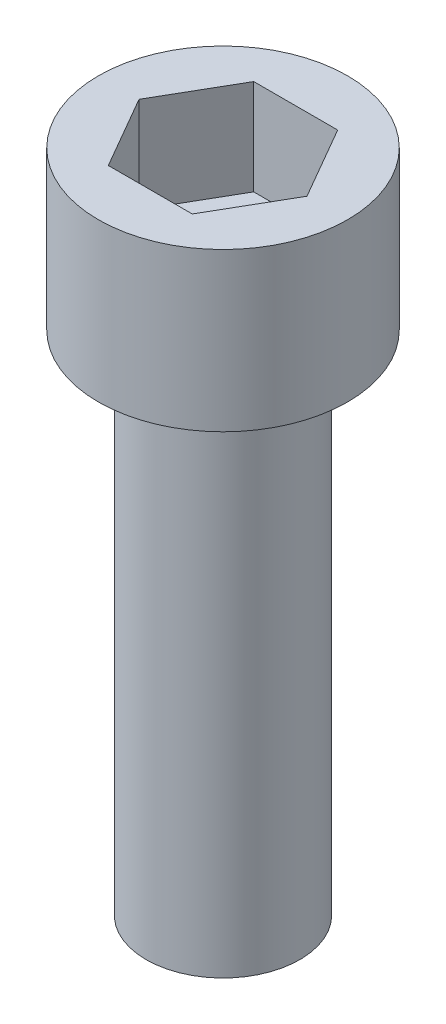
SolidWorks part; units mm, degrees
ref_plane "Front Plane" through (0, 0, 0) normal (0, 0, 1) x (1, 0, 0)
ref_plane "Top Plane" through (0, 0, 0) normal (0, 1, 0) x (1, 0, 0)
ref_plane "Right Plane" through (0, 0, 0) normal (1, 0, 0) x (0, 0, -1)
sketch "Sketch2" plane through (0, 0, 0) normal (1, 0, 0) x (0, 0, -1)
  line L0 (0, 0) -> (2.3495, 0)
  line L1 (2.3495, 0) -> (2.3495, 15.494)
  line L2 (2.3495, 15.494) -> (3.81, 15.494)
  line L3 (3.81, 15.494) -> (3.81, 20.32)
  line L4 (3.81, 20.32) -> (0, 20.32)
  line L5 (0, 20.32) -> (0, 0)
  dimension "D1" = 2.3495
  dimension "D2" = 20.32
  dimension "D3" = 4.826
  dimension "D4" = 3.81
revolve "Revolve1" add sketch "Sketch2" angle 360 about L5
sketch "Sketch3" plane through (0, 20.32, 0) normal (0, 1, 0) x (1, 0, 0)
  line L1 (1.2832, -2.2225) -> (2.5663, 0)
  line L2 (2.5663, 0) -> (1.2832, 2.2225)
  line L3 (1.2832, 2.2225) -> (-1.2832, 2.2225)
  line L4 (-1.2832, 2.2225) -> (-2.5663, 0)
  line L5 (-2.5663, 0) -> (-1.2832, -2.2225)
  line L6 (-1.2832, -2.2225) -> (1.2832, -2.2225)
  circle A0 centre (0, 0) radius 2.2225 construction
  dimension "D1" = 4.445
extrude "Cut-Extrude1" cut sketch "Sketch3" against normal blind 2.921
